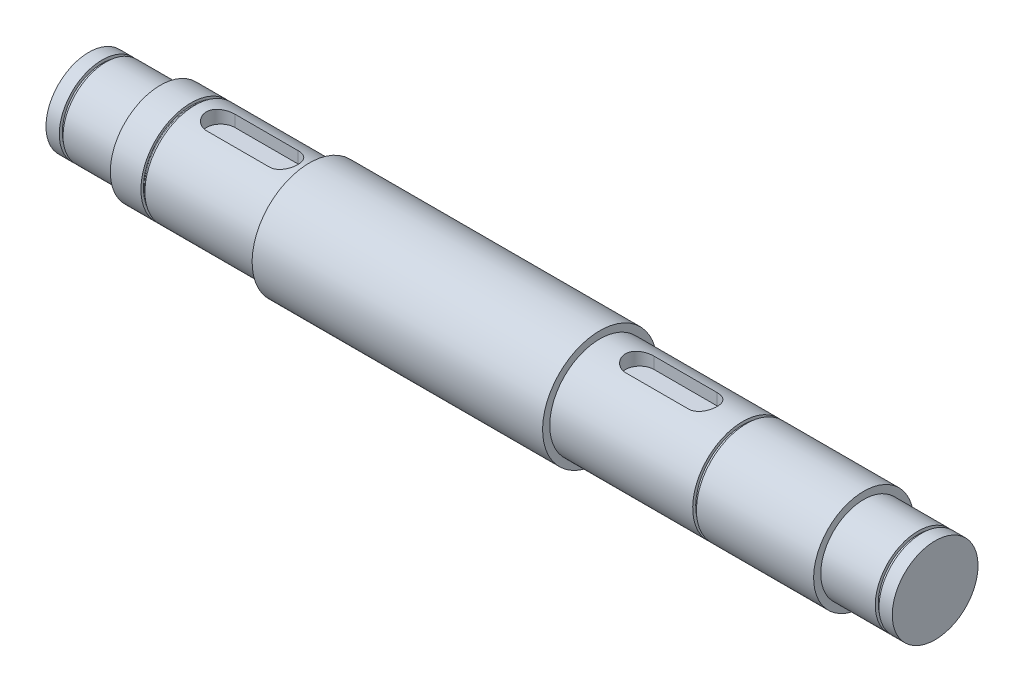
SolidWorks part; units mm, degrees
material "1023 Carbon Steel Sheet (SS)"
ref_plane "Front Plane" through (0, 0, 0) normal (0, 0, 1) x (1, 0, 0)
ref_plane "Top Plane" through (0, 0, 0) normal (0, 1, 0) x (1, 0, 0)
ref_plane "Right Plane" through (0, 0, 0) normal (1, 0, 0) x (0, 0, -1)
sketch "Sketch1" plane through (0, 0, 0) normal (0, 0, 1) x (1, 0, 0)
  line L0 (24.3, 17.0787) -> (5.2604, 17.0787)
  line L1 (24.3, 19.5787) -> (24.3, 17.0787)
  line L2 (178, 22.0787) -> (178, 19.5787)
  line L3 (178, 19.5787) -> (228, 19.5787)
  line L4 (-0.7, 17.0787) -> (-0.7, 2.0787)
  line L5 (-0.7, 2.0787) -> (295.3, 2.0787)
  line L6 (24.3, 19.5787) -> (35, 19.5787)
  line L7 (35, 19.5787) -> (35, 18.7287)
  line L8 (35.2, 18.5287) -> (36.2, 18.5287)
  line L9 (36.4, 18.7287) -> (36.4, 19.5787)
  line L10 (36.4, 19.5787) -> (76.4, 19.5787)
  line L11 (76.4, 19.5787) -> (76.4, 22.0787)
  line L12 (76.4, 22.0787) -> (178, 22.0787)
  line L13 (228, 19.5787) -> (228, 18.5287)
  line L14 (228, 18.5287) -> (229.3, 18.5287)
  line L15 (229.3, 18.5287) -> (229.3, 19.5787)
  line L16 (229.3, 19.5787) -> (270.3, 19.5787)
  line L17 (270.3, 19.5787) -> (270.3, 17.0787)
  line L18 (270.3, 17.0787) -> (289.3597, 17.0787)
  line L19 (295.3, 17.0787) -> (295.3, 2.0787)
  line L20 (5.2604, 17.0787) -> (5.2604, 16.0287)
  line L21 (5.2604, 16.0287) -> (3.9604, 16.0287)
  line L22 (3.9604, 16.0287) -> (3.9604, 17.0787)
  line L23 (3.9604, 17.0787) -> (-0.7, 17.0787)
  line L24 (289.3597, 17.0787) -> (289.3597, 16.0287)
  line L25 (-34.2403, 2.0787) -> (297.8932, 2.0787) construction
  line L26 (289.3597, 16.0287) -> (290.6597, 16.0287)
  line L27 (290.6597, 16.0287) -> (290.6597, 17.0787)
  line L28 (290.6597, 17.0787) -> (295.3, 17.0787)
  arc A0 (35.2, 18.5287) -> (35, 18.7287) centre (35.2, 18.7287) cw
  arc A1 (36.2, 18.5287) -> (36.4, 18.7287) centre (36.2, 18.7287) ccw
  point P31 (35.1, 18.5287)
  point P34 (36.4, 18.5287)
  dimension "D21" = 0.2
  dimension "D3" = 35
  dimension "D4" = 1.3
  dimension "D5" = 1.3
  dimension "D6" = 1.05
  dimension "D7" = 50
  dimension "D8" = 25
  dimension "D9" = 40
  dimension "D10" = 2.5
  dimension "D11" = 25
  dimension "D12" = 40
  dimension "D13" = 41
  dimension "D14" = 1.05
  dimension "D15" = 10.7
  dimension "D16" = 101.6
  dimension "D17" = 1.05
  dimension "D18" = 1.3
  dimension "D19" = 1.05
  dimension "D20" = 1.3
revolve "Revolve1" add sketch "Sketch1" angle 360 about L25
sketch "Sketch4" plane through (0, 0, 0) normal (0, 1, 0) x (1, 0, 0)
  line L0 (45.4, 0) -> (67.4, 0) construction
  line L1 (45.4, 5) -> (67.4, 5)
  line L2 (45.4, -5) -> (67.4, -5)
  line L3 (192, 0) -> (214, 0) construction
  line L4 (192, 5) -> (214, 5)
  line L5 (192, -5) -> (214, -5)
  line L10 (178, -20) -> (178, 20) construction
  line L13 (76.4, 20) -> (76.4, -20) construction
  arc A0 (45.4, 5) -> (45.4, -5) centre (45.4, 0) ccw
  arc A1 (67.4, -5) -> (67.4, 5) centre (67.4, 0) ccw
  arc A2 (192, 5) -> (192, -5) centre (192, 0) ccw
  arc A3 (214, -5) -> (214, 5) centre (214, 0) ccw
  point P3 (56.4, 0)
  point P8 (203, 0)
  point P15 (72.4, 0)
  point P16 (40.4, 0)
  point P19 (219, 0)
  point P20 (187, 0)
  dimension "D5" = 32
  dimension "D1" = 32
  dimension "D2" = 4
  dimension "D3" = 10
  dimension "D4" = 10
  dimension "D6" = 9
extrude "Cut-Extrude3" cut sketch "Sketch4" against normal blind 6.2 from offset 21
